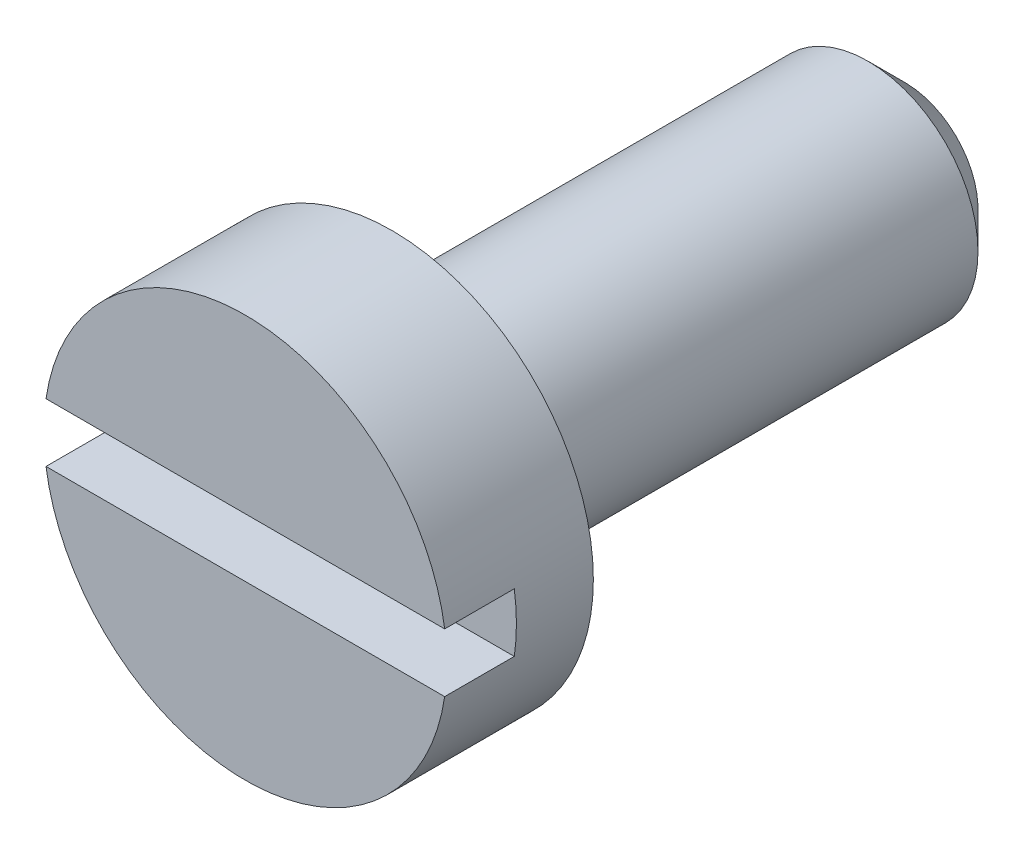
SolidWorks part; units mm, degrees
ref_plane "Спереди" through (0, 0, 0) normal (0, 0, 1) x (1, 0, 0)
ref_plane "Сверху" through (0, 0, 0) normal (0, 1, 0) x (1, 0, 0)
ref_plane "Справа" through (0, 0, 0) normal (1, 0, 0) x (0, 0, -1)
sketch "Эскиз12" plane through (0, 0, 0) normal (0, 0, 1) x (1, 0, 0)
  circle A0 centre (0, 0) radius 2.75
extrude "Вытянуть3" add sketch "Эскиз12" along normal blind 2
sketch "Эскиз13" plane through (0, 0, 0) normal (0, 0, -1) x (-1, 0, 0)
  circle A0 centre (0, 0) radius 1.5
extrude "Вытянуть4" add sketch "Эскиз13" along normal blind 7
sketch "Эскиз14" plane through (0, 0, 2) normal (0, 0, 1) x (1, 0, 0)
  line L0 (-2.75, 0) -> (2.75, 0) construction
  circle A0 centre (0, 0) radius 2.75 construction
sketch "Эскиз20" plane through (0, 0, 2) normal (0, 0, 1) x (1, 0, 0)
  line L0 (-2.75, 0) -> (2.75, 0) construction
  line L1 (-3.0316, 0.4) -> (3.0033, 0.4)
  line L2 (-3.0316, 0.4) -> (-3.0316, -0.4)
  line L3 (-3.0316, -0.4) -> (3.0033, -0.4)
  line L4 (3.0033, 0.4) -> (3.0033, -0.4)
  dimension "D1" = 0.4
  dimension "D2" = 0.4
extrude "Вырез-Вытянуть8" cut sketch "Эскиз20" against normal blind 0.95
chamfer "Фаска1" distance 0.5 angle 45 1 edges at (-1.5, 0, -7)
